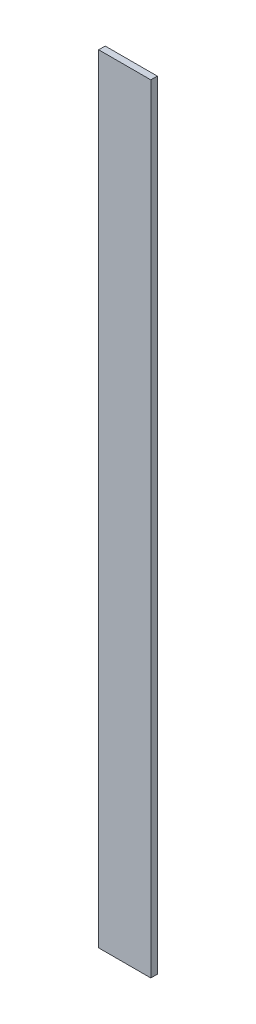
SolidWorks part; units mm, degrees
ref_plane "Front Plane" through (0, 0, 0) normal (0, 0, 1) x (1, 0, 0)
ref_plane "Top Plane" through (0, 0, 0) normal (0, 1, 0) x (1, 0, 0)
ref_plane "Right Plane" through (0, 0, 0) normal (1, 0, 0) x (0, 0, -1)
other "Configuration Table"
sketch "Sketch1" plane through (0, 0, 0) normal (0, 0, 1) x (1, 0, 0)
  line L1 (702, 1469) -> (714, 1469)
  line L2 (702, 1469) -> (702, 1648)
  line L3 (702, 1648) -> (714, 1648)
  line L4 (714, 1469) -> (714, 1648)
extrude "DET_on_sove_dilimi_1" add sketch "Sketch1" along normal blind 1.5 from offset 38.5 separate body
